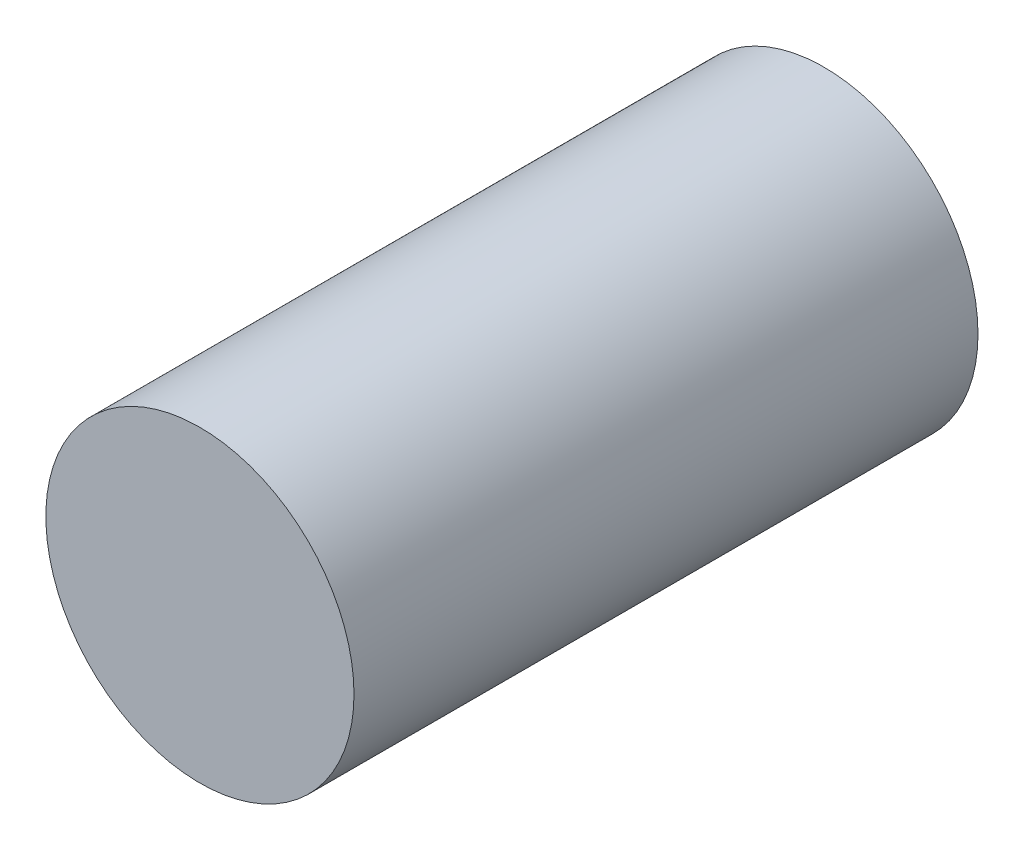
SolidWorks part; units mm, degrees
ref_plane "Front Plane" through (0, 0, 0) normal (0, 0, 1) x (1, 0, 0)
ref_plane "Top Plane" through (0, 0, 0) normal (0, 1, 0) x (1, 0, 0)
ref_plane "Right Plane" through (0, 0, 0) normal (1, 0, 0) x (0, 0, -1)
sketch "Sketch1" plane through (0, 0, 0) normal (0, 0, 1) x (1, 0, 0)
  circle A0 centre (-110.1328, 48.9685) radius 2
extrude "Boss-Extrude1" add sketch "Sketch1" along normal blind 8.1
